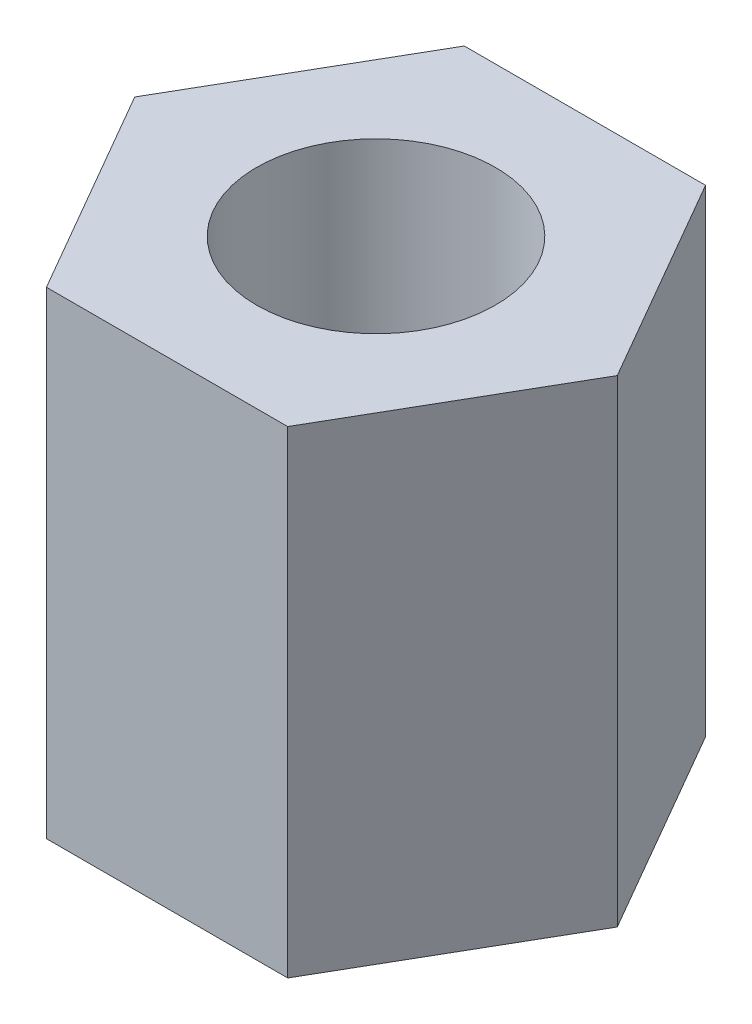
SolidWorks part; units mm, degrees
ref_plane "Front Plane" through (0, 0, 0) normal (0, 0, 1) x (1, 0, 0)
ref_plane "Top Plane" through (0, 0, 0) normal (0, 1, 0) x (1, 0, 0)
ref_plane "Right Plane" through (0, 0, 0) normal (1, 0, 0) x (0, 0, -1)
sketch "Sketch1" plane through (0, 0, 0) normal (0, 1, 0) x (1, 0, 0)
  line L1 (4.0415, 0) -> (2.0207, 3.5)
  line L2 (2.0207, 3.5) -> (-2.0207, 3.5)
  line L3 (-2.0207, 3.5) -> (-4.0415, 0)
  line L4 (-4.0415, 0) -> (-2.0207, -3.5)
  line L5 (-2.0207, -3.5) -> (2.0207, -3.5)
  line L6 (2.0207, -3.5) -> (4.0415, 0)
  circle A0 centre (0, 0) radius 3.5 construction
  circle A1 centre (0, 0) radius 2
  dimension "D1" = 4
  dimension "D2" = 7
extrude "Boss-Extrude1" add sketch "Sketch1" along normal blind 8
